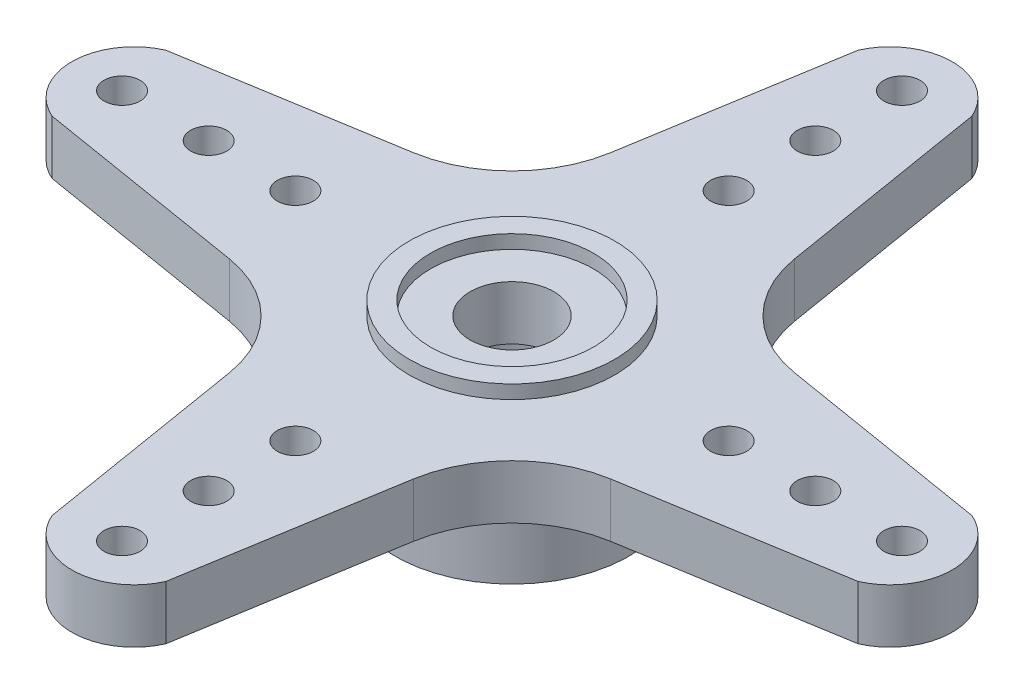
SolidWorks part; units mm, degrees
material "Nylon 6/10"
ref_plane "Front Plane" through (0, 0, 0) normal (0, 0, 1) x (1, 0, 0)
ref_plane "Top Plane" through (0, 0, 0) normal (0, 1, 0) x (1, 0, 0)
ref_plane "Right Plane" through (0, 0, 0) normal (1, 0, 0) x (0, 0, -1)
sketch "Sketch1" plane through (0, 0, 0) normal (0, 1, 0) x (1, 0, 0)
  circle A0 centre (0, 0) radius 4.064
  circle A1 centre (0, 0) radius 2.794
  dimension "D1" = 8.128
  dimension "D2" = 5.588
extrude "Boss-Extrude1" add sketch "Sketch1" along normal blind 3.302
sketch "Sketch2" plane through (0, 3.302, 0) normal (0, 1, 0) x (1, 0, 0)
  line L0 (0, 0) -> (0, -7.5005) construction
  line L1 (6.5981, -3.1844) -> (13.9505, -1.9734)
  line L2 (6.5981, 3.1844) -> (13.9505, 1.9734)
  line L3 (0, 0) -> (3.1844, 6.5981) construction
  line L4 (0, 0) -> (4.1219, 6.0568) construction
  line L5 (0, 0) -> (0, 15.24) construction
  line L6 (0, -7.5005) -> (0, -10.5005) construction
  line L7 (0, -10.5005) -> (0, -13.5005) construction
  line L8 (-3.1844, -6.5981) -> (-1.9734, -13.9505)
  line L9 (3.1844, -6.5981) -> (1.9734, -13.9505)
  line L10 (-6.5981, 3.1844) -> (-13.9505, 1.9734)
  line L11 (-6.5981, -3.1844) -> (-13.9505, -1.9734)
  line L15 (3.1844, 6.5981) -> (1.9734, 13.9505)
  line L16 (-3.1844, 6.5981) -> (-1.9734, 13.9505)
  line L21 (3.1844, -6.5981) -> (1.9734, -13.9505)
  line L22 (-3.1844, -6.5981) -> (-1.9734, -13.9505)
  line L31 (0.002, 0) -> (-3.1824, -6.5981) construction
  line L32 (0.002, 0) -> (-4.1199, -6.0568) construction
  line L33 (0.0015, -0.0009) -> (-7.3048, -0.5421) construction
  line L34 (0.0015, -0.0009) -> (-7.3048, 0.5404) construction
  line L35 (0.0005, -0.0009) -> (-4.1214, 6.056) construction
  line L36 (0.0005, -0.0009) -> (-3.1839, 6.5972) construction
  line L37 (0.0015, 0.0009) -> (4.1234, -6.056) construction
  line L38 (0.0015, 0.0009) -> (3.1859, -6.5972) construction
  line L39 (0.0005, 0.0009) -> (7.3068, 0.5421) construction
  line L40 (0.0005, 0.0009) -> (7.3068, -0.5404) construction
  line L41 (4.1219, 6.0568) -> (11.0948, 8.6843) [skipped]
  line L42 (7.3063, 0.5413) -> (13.0682, 5.2662) [skipped]
  line L43 (7.3063, -0.5413) -> (13.0682, -5.2662) [skipped]
  line L44 (4.1219, -6.0568) -> (11.0948, -8.6843) [skipped]
  line L45 (-4.1219, -6.0568) -> (-11.0948, -8.6843) [skipped]
  line L46 (-7.3063, -0.5413) -> (-13.0682, -5.2662) [skipped]
  line L47 (-7.3063, 0.5413) -> (-13.0682, 5.2662) [skipped]
  line L48 (-4.1219, 6.0568) -> (-11.0948, 8.6843) [skipped]
  arc A0 (-1.9734, 13.9505) -> (1.9734, 13.9505) centre (0, 13.0852) cw
  arc A3 (1.9734, -13.9505) -> (-1.9734, -13.9505) centre (0, -13.0852) cw
  circle A12 centre (0, -7.5005) radius 0.625
  circle A13 centre (0, -10.5005) radius 0.625
  circle A14 centre (0, -13.5005) radius 0.625
  circle A21 centre (0, 13.5005) radius 0.625
  circle A22 centre (0, 10.5005) radius 0.625
  circle A23 centre (0, 7.5005) radius 0.625
  arc A30 (11.0948, 8.6843) -> (13.0682, 5.2662) centre (11.3321, 6.5426) cw [skipped]
  arc A31 (13.0682, -5.2662) -> (11.0948, -8.6843) centre (11.3321, -6.5426) cw [skipped]
  circle A32 centre (7.5005, 0) radius 0.625
  circle A33 centre (11.6917, 6.7502) radius 0.625 [skipped]
  circle A34 centre (9.0937, 5.2502) radius 0.625 [skipped]
  circle A35 centre (6.4956, 3.7502) radius 0.625 [skipped]
  circle A36 centre (11.6917, -6.7502) radius 0.625 [skipped]
  circle A37 centre (9.0937, -5.2502) radius 0.625 [skipped]
  circle A38 centre (6.4956, -3.7502) radius 0.625 [skipped]
  arc A39 (-11.0948, -8.6843) -> (-13.0682, -5.2662) centre (-11.3321, -6.5426) cw [skipped]
  arc A40 (-13.0682, 5.2662) -> (-11.0948, 8.6843) centre (-11.3321, 6.5426) cw [skipped]
  circle A41 centre (10.5005, 0) radius 0.625
  circle A42 centre (-11.6917, -6.7502) radius 0.625 [skipped]
  circle A43 centre (-9.0937, -5.2502) radius 0.625 [skipped]
  circle A44 centre (-6.4956, -3.7502) radius 0.625 [skipped]
  circle A45 centre (-11.6917, 6.7502) radius 0.625 [skipped]
  circle A46 centre (-9.0937, 5.2502) radius 0.625 [skipped]
  circle A47 centre (-6.4956, 3.7502) radius 0.625 [skipped]
  circle A48 centre (13.5005, 0) radius 0.625
  arc A49 (13.9505, 1.9734) -> (13.9505, -1.9734) centre (13.0852, 0) cw
  circle A50 centre (0, -7.5005) radius 0.625
  circle A51 centre (0, -10.5005) radius 0.625
  circle A52 centre (0, -13.5005) radius 0.625
  arc A53 (1.9734, -13.9505) -> (-1.9734, -13.9505) centre (0, -13.0852) cw
  circle A54 centre (-7.5005, 0) radius 0.625
  circle A55 centre (-10.5005, 0) radius 0.625
  circle A56 centre (-13.5005, 0) radius 0.625
  arc A57 (-13.9505, -1.9734) -> (-13.9505, 1.9734) centre (-13.0852, 0) cw
  arc A58 (3.1844, 6.5981) -> (6.5981, 3.1844) centre (7.2712, 7.2712) ccw
  arc A59 (6.5981, -3.1844) -> (3.1844, -6.5981) centre (7.2712, -7.2712) ccw
  arc A60 (-3.1844, -6.5981) -> (-6.5981, -3.1844) centre (-7.2712, -7.2712) ccw
  arc A61 (-6.5981, 3.1844) -> (-3.1844, 6.5981) centre (-7.2712, 7.2712) ccw
  point P4 (0, 0)
  point P12 (0, 0)
  point P16 (0.0005, 0.0009)
  point P20 (0.0015, 0.0009)
  point P24 (0.002, 0)
  point P28 (0.0015, -0.0009)
  point P32 (0.0005, -0.0009)
  point P35 (0.001, 0)
  point P38 (0, 15.24)
  point P59 (0, 0)
  point P72 (0, 0)
  point P76 (0, 0)
  point P82 (0, 0)
  point P83 (0, 0)
  point P110 (0, 0)
  circle M26 centre (0, 0) radius 4.064
  circle M27 centre (0, 0) radius 2.794
  dimension "D5" = 6
  dimension "D2" = 4
  dimension "D3" = 7.3263
  dimension "D7" = 7.4515
  dimension "D12" = 3
  dimension "D6" = 6
  dimension "D9" = 6
  dimension "D10" = 6
extrude "Boss-Extrude2" add sketch "Sketch2" along normal blind 1.87 contours A61 L10 A57 L11 A60 L8 A3 L9 A59 L1 A49 L2 A58 L15 A0 L16 A56 A55 A54 A48 A41 A32 A23 A22 A21 A14 A13 A12 M26 | M26 M27 | M27
sketch "Sketch6" plane through (0, 5.172, 0) normal (0, 1, 0) x (1, 0, 0)
  circle A0 centre (0, 0) radius 1.45
  dimension "D1" = 2.9
extrude "Cut-Extrude6" cut sketch "Sketch6" against normal through all
sketch "Sketch7" plane through (0, 5.172, 0) normal (0, 1, 0) x (1, 0, 0)
  circle A1 centre (0, 0) radius 3.555
  circle A4 centre (0, 0) radius 2.82
extrude "Boss-Extrude3" add sketch "Sketch7" along normal blind 0.47
